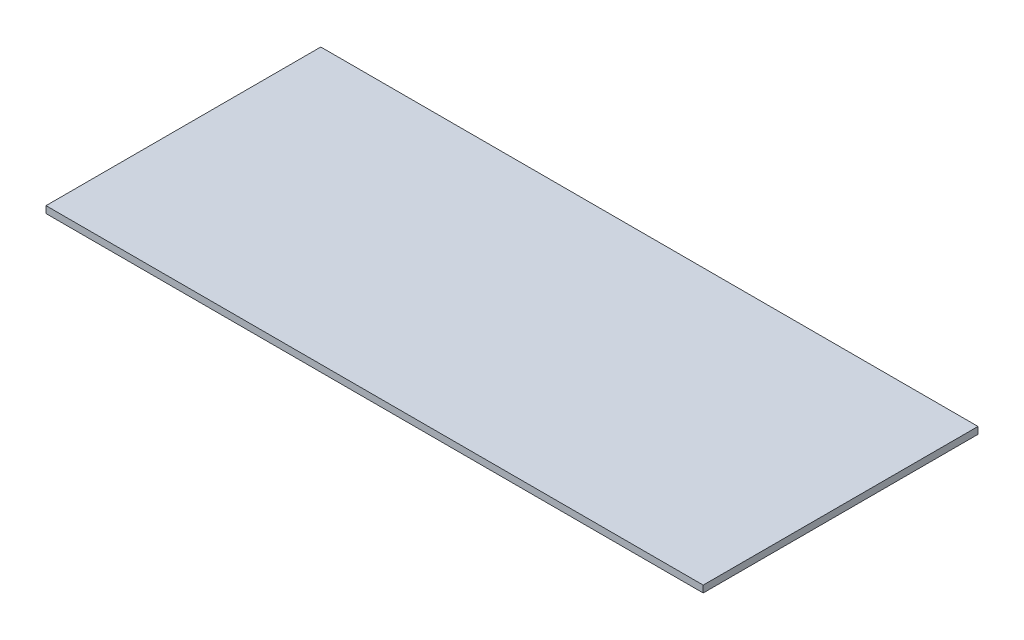
SolidWorks part; units mm, degrees
material "Acrílico (Impacto medio-alto)"
ref_plane "Alzado" through (0, 0, 0) normal (0, 0, 1) x (1, 0, 0)
ref_plane "Planta" through (0, 0, 0) normal (0, 1, 0) x (1, 0, 0)
ref_plane "Vista lateral" through (0, 0, 0) normal (1, 0, 0) x (0, 0, -1)
sketch "Sketch1" plane through (0, 0, 0) normal (0, 1, 0) x (1, 0, 0)
  line L1 (-143.5, -60) -> (143.5, -60)
  line L2 (-143.5, -60) -> (-143.5, 60)
  line L3 (-143.5, 60) -> (143.5, 60)
  line L4 (143.5, -60) -> (143.5, 60)
  line L5 (-143.5, -60) -> (143.5, 60) construction
  line L6 (-143.5, 60) -> (143.5, -60) construction
  point P0 (0, 0)
  dimension "D1" = 120
  dimension "D2" = 287
extrude "Boss-Extrude1" add sketch "Sketch1" along normal blind 3
